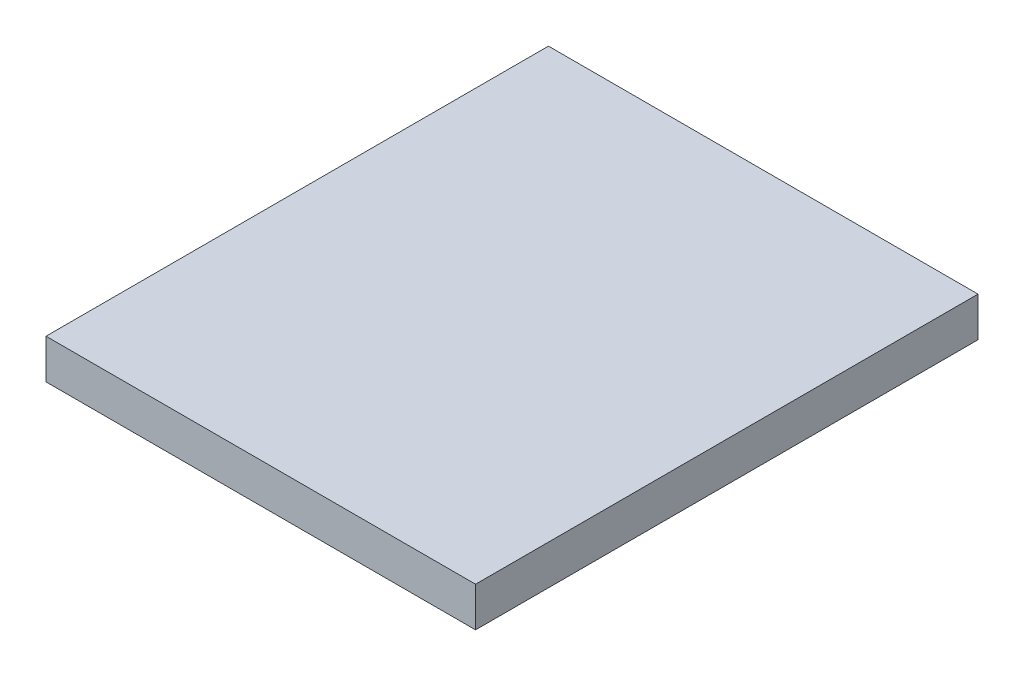
SolidWorks part; units mm, degrees
material "6061 Alloy"
ref_plane "Front" through (0, 0, 0) normal (0, 0, 1) x (1, 0, 0)
ref_plane "Top" through (0, 0, 0) normal (0, 1, 0) x (1, 0, 0)
ref_plane "Right" through (0, 0, 0) normal (1, 0, 0) x (0, 0, -1)
sketch "Sketch1" plane through (0, 0, 0) normal (0, 1, 0) x (1, 0, 0)
  line L1 (-76, 88.9) -> (76, 88.9)
  line L2 (-76, 88.9) -> (-76, -88.9)
  line L3 (-76, -88.9) -> (76, -88.9)
  line L4 (76, 88.9) -> (76, -88.9)
  line L5 (-76, 88.9) -> (76, -88.9) construction
  line L6 (-76, -88.9) -> (76, 88.9) construction
  point P0 (0, 0)
  dimension "D1" = 152
  dimension "D2" = 177.8
extrude "Boss-Extrude1" add sketch "Sketch1" along normal blind 14
